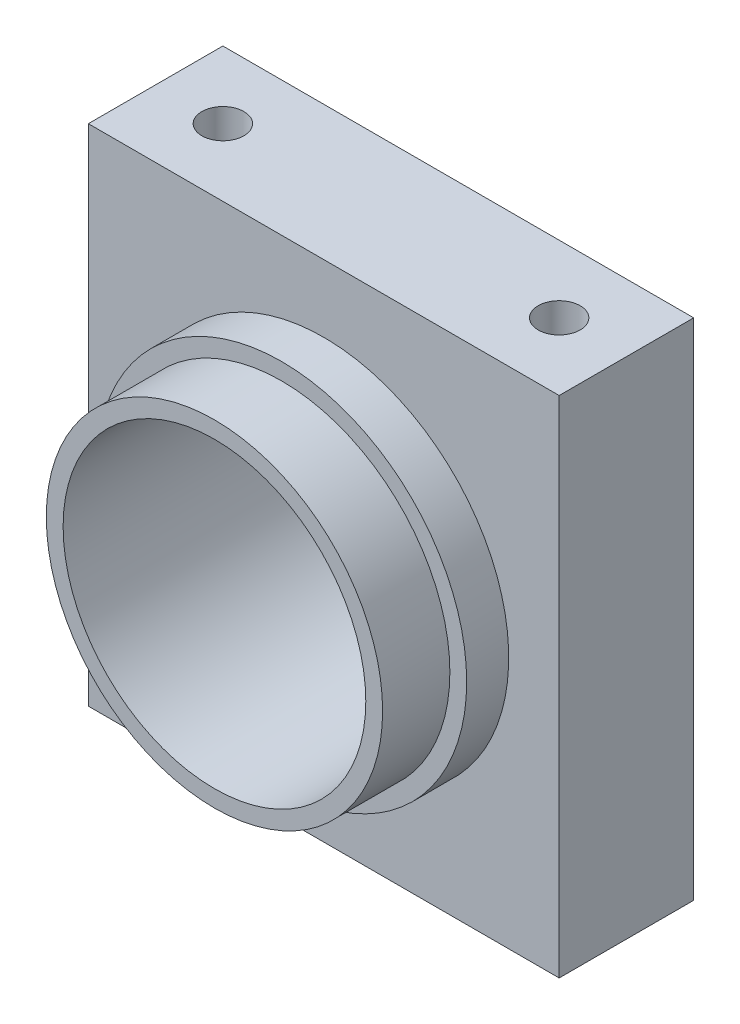
SolidWorks part; units mm, degrees
material "6063-T4"
ref_plane "前视基准面" through (0, 0, 0) normal (0, 0, 1) x (1, 0, 0)
ref_plane "上视基准面" through (0, 0, 0) normal (0, 1, 0) x (1, 0, 0)
ref_plane "右视基准面" through (0, 0, 0) normal (1, 0, 0) x (0, 0, -1)
sketch "草图1" plane through (0, 0, 0) normal (0, 0, 1) x (1, 0, 0)
  line L1 (-14, -15) -> (14, -15)
  line L2 (-14, -15) -> (-14, 15)
  line L3 (-14, 15) -> (14, 15)
  line L4 (14, -15) -> (14, 15)
  line L5 (-14, -15) -> (14, 15) construction
  line L6 (-14, 15) -> (14, -15) construction
  circle A0 centre (0, 0) radius 9
  point P0 (0, 0)
  dimension "D1" = 18
  dimension "D2" = 30
  dimension "D3" = 28
extrude "凸台-拉伸1" add sketch "草图1" along normal blind 8
sketch "草图2" plane through (0, 0, 8) normal (0, 0, 1) x (1, 0, 0)
  circle A0 centre (0, 0) radius 9
  circle A1 centre (0, 0) radius 11
  circle A2 centre (0, 0) radius 9 construction
  dimension "D1" = 22
extrude "凸台-拉伸2" add sketch "草图2" along normal blind 2.5
sketch "草图3" plane through (0, 0, 10.5) normal (0, 0, 1) x (1, 0, 0)
  circle A0 centre (0, 0) radius 9 construction
  circle A1 centre (0, 0) radius 9
  circle A2 centre (0, 0) radius 10
  dimension "D1" = 20
extrude "凸台-拉伸3" add sketch "草图3" along normal blind 4
hole_wizard "M3 螺纹孔1" positions "草图4" profile "草图5" tap size "M3" standard "GB"
sketch "草图4" plane through (0, 15, 0) normal (0, 1, 0) x (1, 0, 0)
  line L0 (-10, -4) -> (10, -4)
  line L2 (14, -8) -> (14, 0) construction
  point P0 (-10, -4)
  point P2 (10, -4)
  point P9 (0, -4)
  point P12 (14, -4)
  dimension "D1" = 20
sketch "草图5" plane through (-10, 15, 4) normal (1, 0, 0) x (0, 0, 1)
  line L0 (0, 0) -> (0, 10.7511)
  line L1 (0, 10.7511) -> (1.25, 10)
  line L2 (1.25, 10) -> (1.25, 0)
  line L5 (1.25, 0) -> (0, 0)
  line L10 (0, 10.7511) -> (-1.25, 10) construction
  line L11 (0, -6.35) -> (0, 107.95) construction
  dimension "螺纹孔钻头直径" = 2.5
  dimension "螺纹孔钻头深度" = 10
  dimension "导头角度" = 118
cosmetic thread "孔螺蚊线1" parameters "D1"=3.5, "D2"=3
cosmetic thread "孔螺蚊线2" parameters "D1"=3.5, "D2"=3
hole_wizard "M3 螺纹孔2" positions "草图6" profile "草图7" tap size "M3" standard "GB"
sketch "草图6" plane through (0, -15, 0) normal (0, -1, 0) x (-1, 0, 0)
  line L0 (-10, -4) -> (10, -4)
  line L2 (14, -8) -> (14, 0) construction
  point P0 (-10, -4)
  point P2 (10, -4)
  point P9 (0, -4)
  point P12 (14, -4)
  dimension "D1" = 20
sketch "草图7" plane through (10, -15, 4) normal (1, 0, 0) x (0, 0, -1)
  line L0 (0, 0) -> (0, 10.7511)
  line L1 (0, 10.7511) -> (1.25, 10)
  line L2 (1.25, 10) -> (1.25, 0)
  line L5 (1.25, 0) -> (0, 0)
  line L10 (0, 10.7511) -> (-1.25, 10) construction
  line L11 (0, -6.35) -> (0, 107.95) construction
  dimension "螺纹孔钻头直径" = 2.5
  dimension "螺纹孔钻头深度" = 10
  dimension "导头角度" = 118
cosmetic thread "孔螺蚊线3" parameters "D1"=3.5, "D2"=3
cosmetic thread "孔螺蚊线4" parameters "D1"=3.5, "D2"=3
